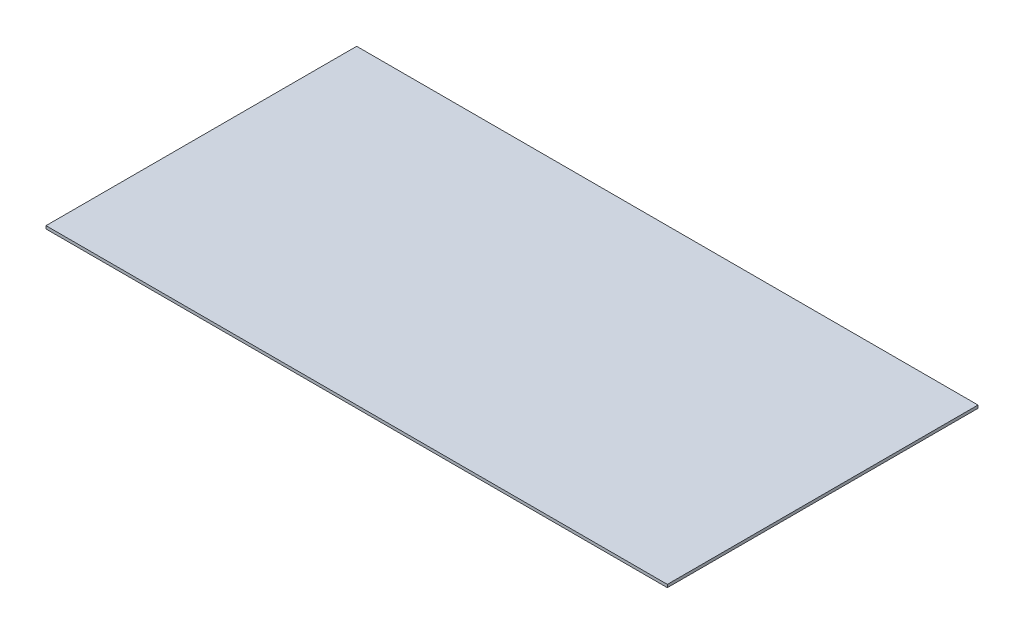
SolidWorks part; units mm, degrees
ref_plane "Front Plane" through (0, 0, 0) normal (0, 0, 1) x (1, 0, 0)
ref_plane "Top Plane" through (0, 0, 0) normal (0, 1, 0) x (1, 0, 0)
ref_plane "Right Plane" through (0, 0, 0) normal (1, 0, 0) x (0, 0, -1)
sketch "Sketch1" plane through (0, 0, 0) normal (0, 1, 0) x (1, 0, 0)
  line L1 (-45, -22.5) -> (45, -22.5)
  line L2 (-45, -22.5) -> (-45, 22.5)
  line L3 (-45, 22.5) -> (45, 22.5)
  line L4 (45, -22.5) -> (45, 22.5)
  line L5 (-45, -22.5) -> (45, 22.5) construction
  line L6 (-45, 22.5) -> (45, -22.5) construction
  point P0 (0, 0)
  dimension "D1" = 45
  dimension "D2" = 90
extrude "Boss-Extrude1" add sketch "Sketch1" along normal blind 0.42
